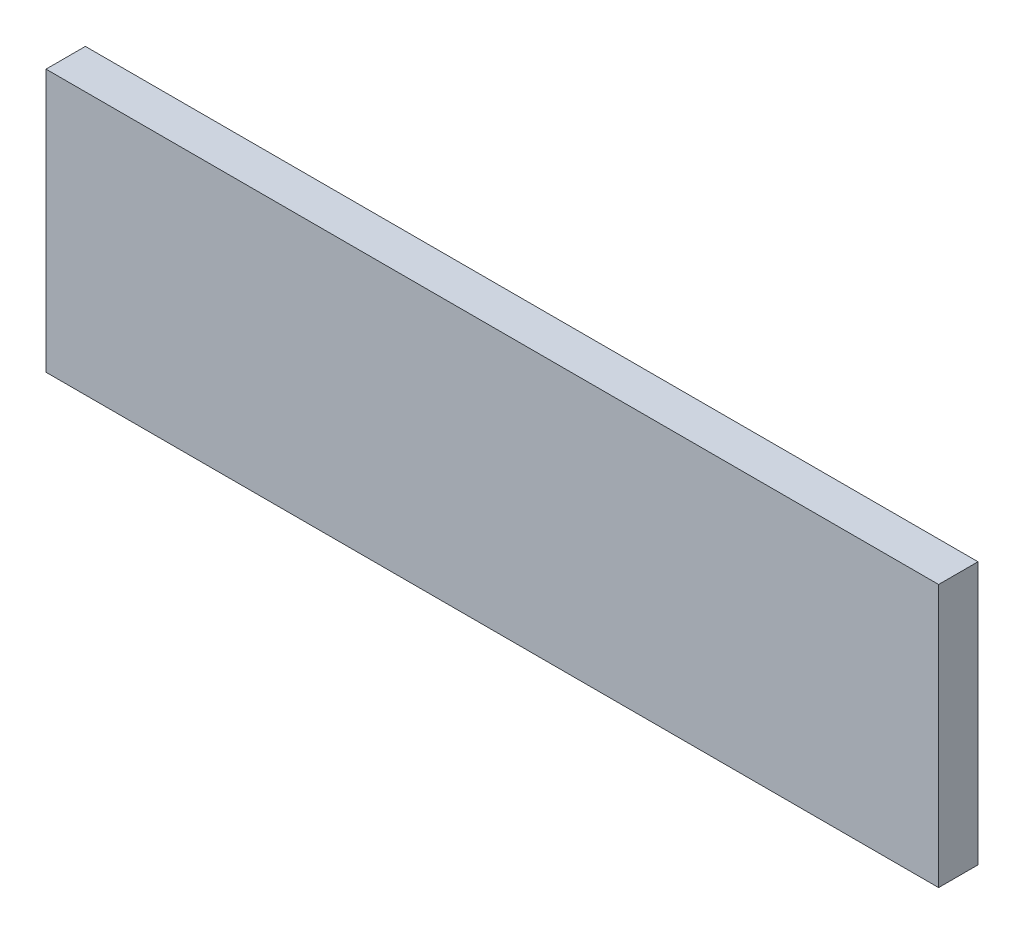
SolidWorks part; units mm, degrees
material "Pine"
ref_plane "Front Plane" through (0, 0, 0) normal (0, 0, 1) x (1, 0, 0)
ref_plane "Top Plane" through (0, 0, 0) normal (0, 1, 0) x (1, 0, 0)
ref_plane "Right Plane" through (0, 0, 0) normal (1, 0, 0) x (0, 0, -1)
sketch "Sketch1" plane through (0, 0, 0) normal (0, 0, 1) x (1, 0, 0)
  line L1 (0, 0) -> (431.8, 0)
  line L2 (0, 0) -> (0, 127)
  line L3 (0, 127) -> (431.8, 127)
  line L4 (431.8, 0) -> (431.8, 127)
  dimension "D1" = 127
  dimension "D2" = 431.8
extrude "Boss-Extrude1" add sketch "Sketch1" along normal blind 19.05
